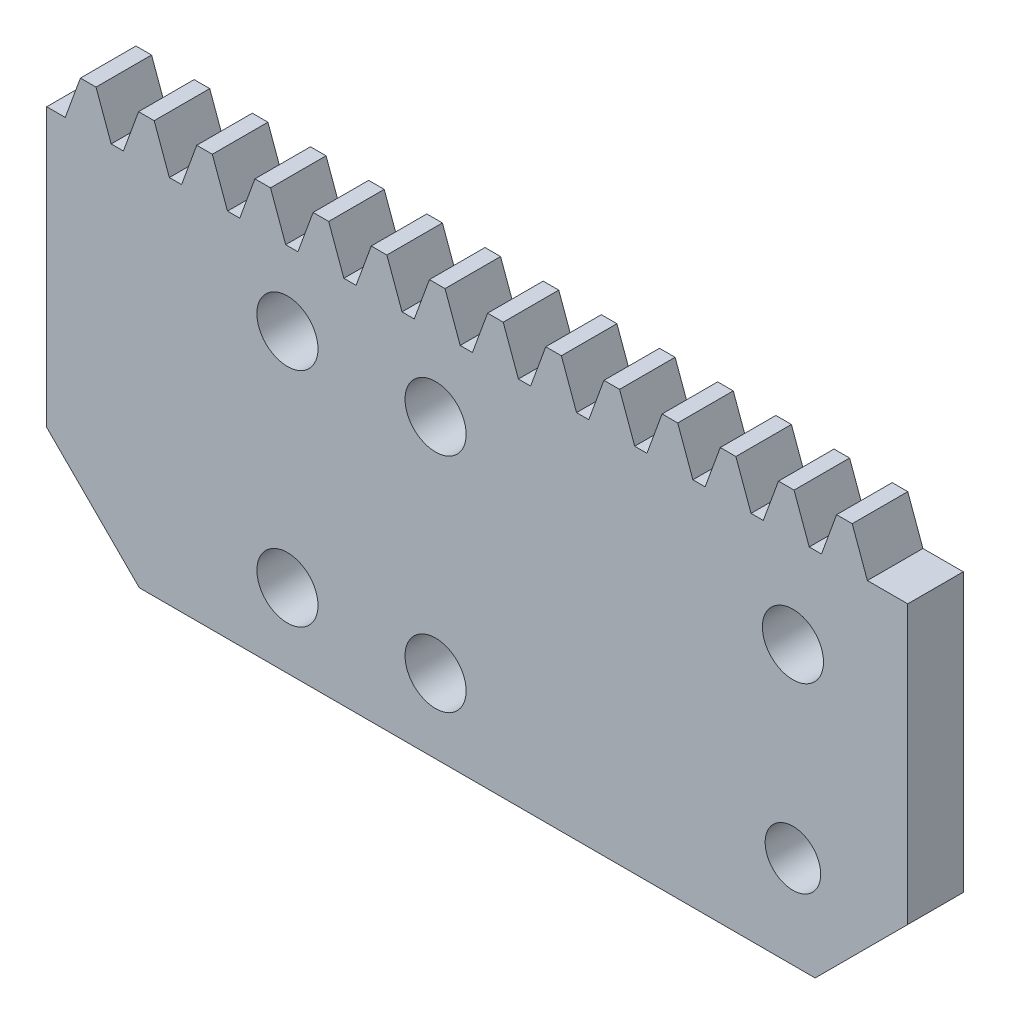
SolidWorks part; units mm, degrees
ref_plane "前基準面" through (0, 0, 0) normal (0, 0, 1) x (1, 0, 0)
ref_plane "上基準面" through (0, 0, 0) normal (0, 1, 0) x (1, 0, 0)
ref_plane "右基準面" through (0, 0, 0) normal (1, 0, 0) x (0, 0, -1)
sketch "草圖1" plane through (0, 0, 0) normal (0, 0, 1) x (1, 0, 0)
  line L1 (-23.25, -10) -> (23.25, -10)
  line L2 (-23.25, -10) -> (-23.25, 10)
  line L3 (-23.25, 10) -> (23.25, 10)
  line L4 (23.25, -10) -> (23.25, 10)
  line L5 (-23.25, -10) -> (23.25, 10) construction
  line L6 (-23.25, 10) -> (23.25, -10) construction
  point P0 (0, 0)
  dimension "D1" = 20
  dimension "D2" = 46.5
extrude "填料-伸長1" add sketch "草圖1" along normal blind 3
sketch "草圖2" plane through (0, 0, 3) normal (0, 0, 1) x (1, 0, 0)
  line L0 (-22.25, 10) -> (-21.4311, 12.25)
  line L1 (23.25, 10) -> (-23.25, 10) construction
  line L2 (-21.4311, 12.25) -> (-20.5882, 12.25)
  line L3 (-20.5882, 12.25) -> (-19.7693, 10)
  line L4 (-22.25, 10) -> (-19.7693, 10)
  line L5 (-21.795, 11.25) -> (-20.2242, 11.25) construction
  dimension "D1" = 1
  dimension "D2" = 1.5708
  dimension "D3" = 2.25
  dimension "D4" = 1
  dimension "D5" = 40
extrude "填料-伸長2" add sketch "草圖2" against normal blind 3
pattern_linear "直線複製排列1" count 14 spacing 3.1416 along (1, 0, 0) of "填料-伸長2"
sketch "草圖3" plane through (0, 0, 3) normal (0, 0, 1) x (1, 0, 0)
  line L0 (-23.25, 10) -> (-23.25, -10) construction
  line L1 (-10.25, 6) -> (-2.25, 6) construction
  line L2 (-10.25, 6) -> (-10.25, -6) construction
  line L3 (-10.25, -6) -> (-2.25, -6) construction
  line L4 (-2.25, 6) -> (-2.25, -6) construction
  circle A0 centre (-10.25, 6) radius 1.65
  circle A1 centre (-2.25, 6) radius 1.65
  circle A2 centre (-2.25, -6) radius 1.65
  circle A3 centre (-10.25, -6) radius 1.65
  point P10 (-10.25, 0)
  point P11 (-23.25, 0)
  dimension "D1" = 3.3
  dimension "D2" = 3.3
  dimension "D3" = 3.3
  dimension "D4" = 3.3
  dimension "D5" = 12
  dimension "D6" = 8
  dimension "D7" = 13
extrude "除料-伸長1" cut sketch "草圖3" against normal blind 3
sketch "草圖4" plane through (0, 0, 3) normal (0, 0, 1) x (1, 0, 0)
  line L0 (17.05, 5) -> (17.05, -5) construction
  line L1 (23.25, -10) -> (23.25, 10) construction
  circle A0 centre (17.05, 5) radius 1.65
  circle A1 centre (17.05, -5) radius 1.5
  point P6 (17.05, 0)
  dimension "D1" = 3.3
  dimension "D2" = 3
  dimension "D3" = 6.2
  dimension "D4" = 10
extrude "除料-伸長2" cut sketch "草圖4" against normal blind 10
chamfer "導角1" distance 5 angle 45 2 edges at (-23.25, -10, 1.5) (23.25, -10, 1.5)
